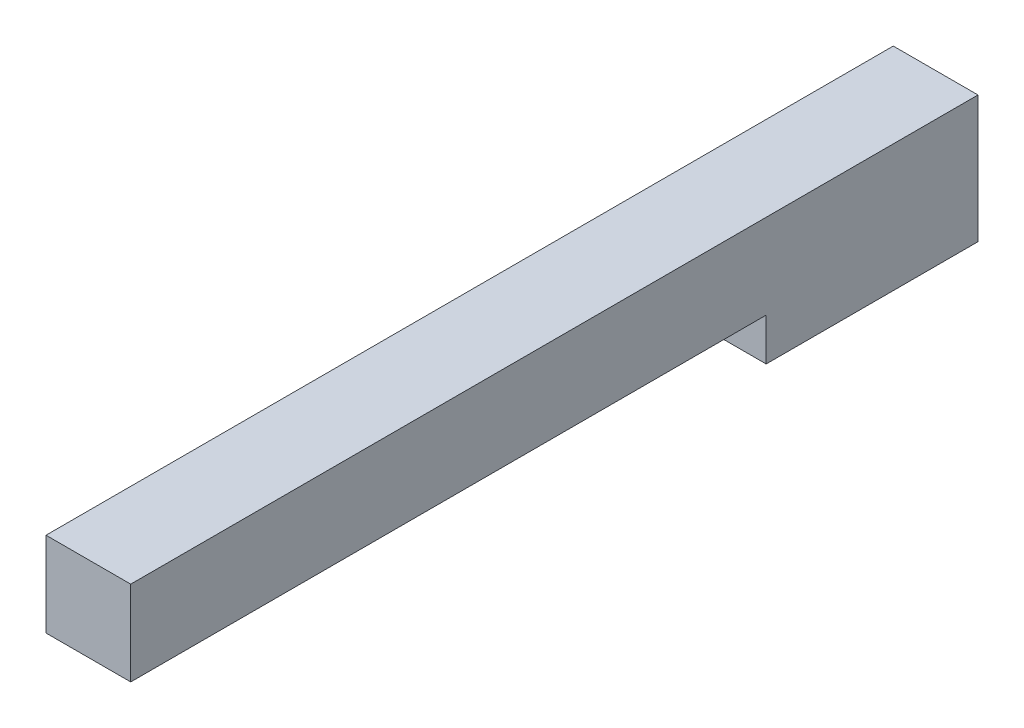
SolidWorks part; units mm, degrees
ref_plane "Alzado" through (0, 0, 0) normal (0, 0, 1) x (1, 0, 0)
ref_plane "Planta" through (0, 0, 0) normal (0, 1, 0) x (1, 0, 0)
ref_plane "Vista lateral" through (0, 0, 0) normal (1, 0, 0) x (0, 0, -1)
sketch "Croquis11" plane through (0, 0, 0) normal (0, 0, 1) x (1, 0, 0)
  line L1 (-2, 3) -> (2, 3)
  line L2 (-2, 3) -> (-2, -3)
  line L3 (-2, -3) -> (2, -3)
  line L4 (2, 3) -> (2, -3)
  line L5 (-2, 3) -> (2, -3) construction
  line L6 (-2, -3) -> (2, 3) construction
  point P0 (0, 0)
  dimension "D1" = 6
  dimension "D2" = 4
extrude "Saliente-Extruir5" add sketch "Croquis11" along normal blind 10
sketch "Croquis12" plane through (0, 0, 10) normal (0, 0, 1) x (1, 0, 0)
  line L0 (2, -3) -> (2, 3) construction
  line L1 (-2, 3) -> (2, 3)
  line L2 (-2, 3) -> (-2, -1)
  line L3 (-2, -1) -> (2, -1)
  line L4 (2, 3) -> (2, -1)
  dimension "D1" = 4
extrude "Saliente-Extruir6" add sketch "Croquis12" along normal blind 30
